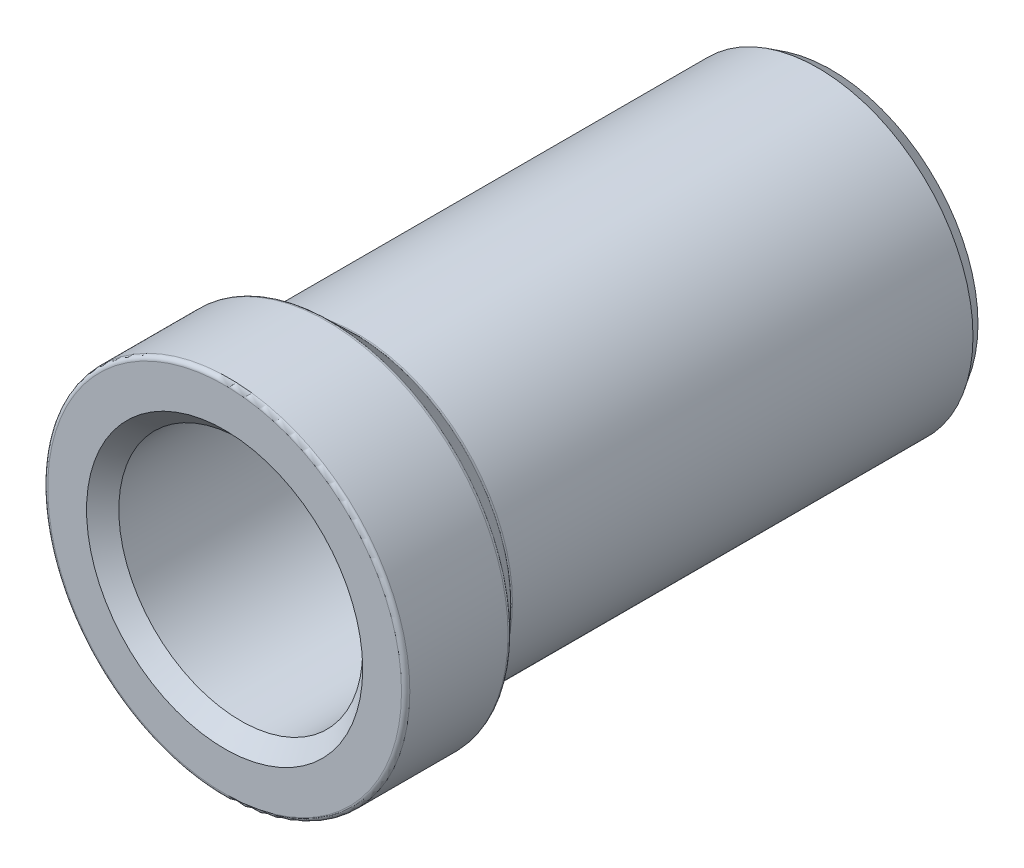
SolidWorks part; units mm, degrees
material "AISI 4130 Steel, normalized at 870C"
ref_plane "Front Plane" through (0, 0, 0) normal (0, 0, 1) x (1, 0, 0)
ref_plane "Top Plane" through (0, 0, 0) normal (0, 1, 0) x (1, 0, 0)
ref_plane "Right Plane" through (0, 0, 0) normal (1, 0, 0) x (0, 0, -1)
sketch "Sketch1" plane through (0, 0, 0) normal (0, 0, 1) x (1, 0, 0)
  circle A0 centre (0, 0) radius 18.923
  dimension "D1" = 37.846
extrude "Boss-Extrude1" add sketch "Sketch1" along normal blind 74.041
sketch "Sketch3" plane through (0, 0, 0) normal (0, 1, 0) x (1, 0, 0)
  line L0 (0, 0) -> (0, -74.041) construction
  line L1 (-18.923, -74.041) -> (18.923, -74.041) construction
  line L2 (0, -74.041) -> (22.098, -74.041)
  line L3 (22.098, -74.041) -> (22.098, -61.341)
  line L4 (22.098, -61.341) -> (18.923, -58.039)
  line L5 (18.923, -74.041) -> (18.923, 0) construction
  line L6 (18.923, -58.039) -> (0, -58.039)
  line L7 (0, -58.039) -> (0, -74.041)
  dimension "D1" = 22.098
  dimension "D2" = 12.7
  dimension "D3" = 16.002
revolve "Revolve1" add sketch "Sketch3" angle 360 about L0
fillet "Fillet1" radius 0.508 3 edges at (-22.098, 0, 74.041) (18.923, 0, 58.039) (-22.098, 0, 61.341)
chamfer "Chamfer1" distance 1.016 angle 58 1 edges at (18.923, 0, 0)
sketch "Sketch4" plane through (0, 0, 0) normal (0, 0, -1) x (-1, 0, 0)
  circle A0 centre (0, 0) radius 14.859
  circle A1 centre (0, 0) radius 17.907 construction
  dimension "D1" = 29.718
extrude "Cut-Extrude1" cut sketch "Sketch4" along a picked direction on the side against the normal blind 12.7
chamfer "Chamfer2" distance 0.762 angle 45 1 edges at (-14.859, 0, 0)
ref_point "Point1"
hole_wizard "1-1/4-12 Tapped Hole1" positions "Sketch6" profile "Sketch5" tap size "1-1/4-12" standard "Ansi Inch"
sketch "Sketch6" plane through (0, 0, 74.041) normal (0, 0, 1) x (1, 0, 0)
  circle A0 centre (0, 0) radius 21.59 construction
  point P0 (0, 0)
cosmetic thread "Hole Thread1" parameters "D2"=31.75
sketch "Sketch5" plane through (0, 0, 74.041) normal (1, 0, 0) x (0, -1, 0)
  line L0 (0, 0) -> (0, 61.341)
  line L1 (0, 61.341) -> (14.8831, 61.341)
  line L2 (14.8831, 61.341) -> (14.8831, 1.9698)
  line L3 (14.8831, 1.9698) -> (16.8529, 0)
  line L5 (16.8529, 0) -> (0, 0)
  line L6 (-14.8831, 1.9698) -> (-16.8529, 0) construction
  line L11 (0, -6.35) -> (0, 107.95) construction
  dimension "Thru Tap Drill Dia." = 29.7663
  dimension "Thru Tap Drill Depth" = 61.341
  dimension "Near C'Sink Dia." = 33.7058
  dimension "Near C'Sink Angle" = 90
